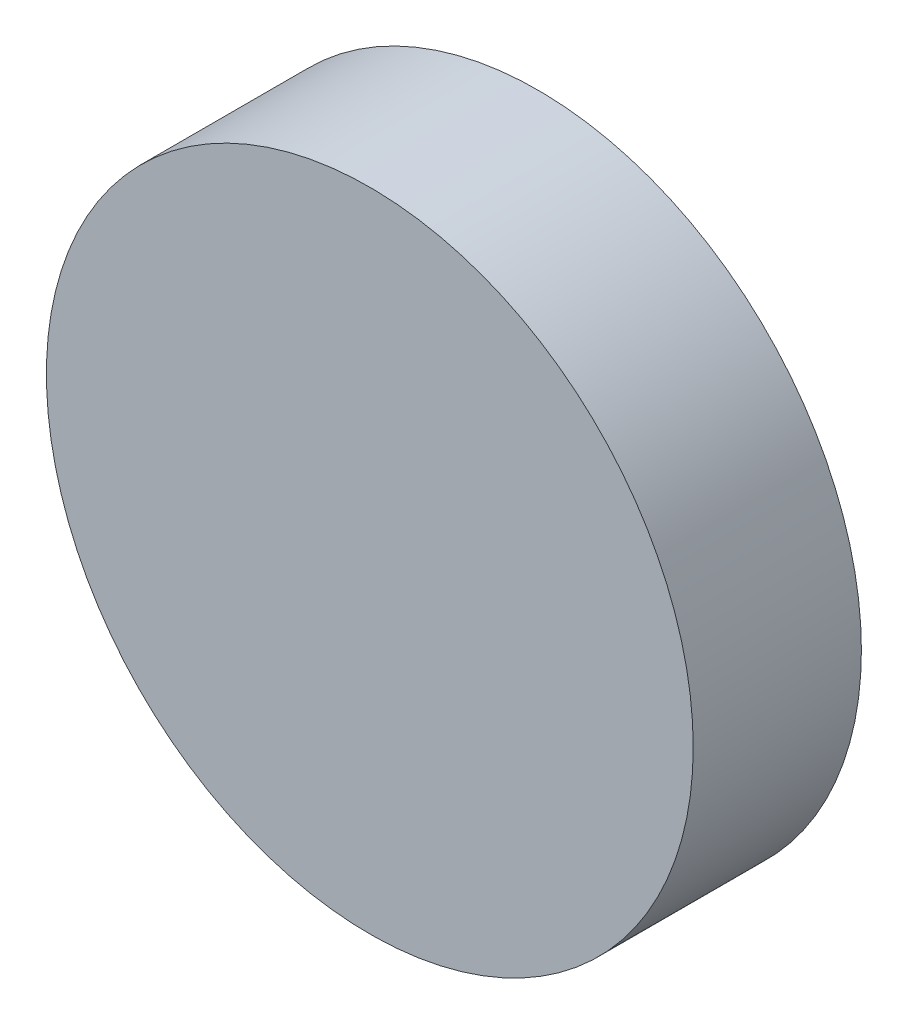
SolidWorks part; units mm, degrees
ref_plane "Front Plane" through (0, 0, 0) normal (0, 0, 1) x (1, 0, 0)
ref_plane "Top Plane" through (0, 0, 0) normal (0, 1, 0) x (1, 0, 0)
ref_plane "Right Plane" through (0, 0, 0) normal (1, 0, 0) x (0, 0, -1)
sketch "Sketch1" plane through (0, 0, 0) normal (0, 0, 1) x (1, 0, 0)
  circle A0 centre (0, 0) radius 50
  dimension "D1" = 100
extrude "Boss-Extrude1" add sketch "Sketch1" along normal blind 26
